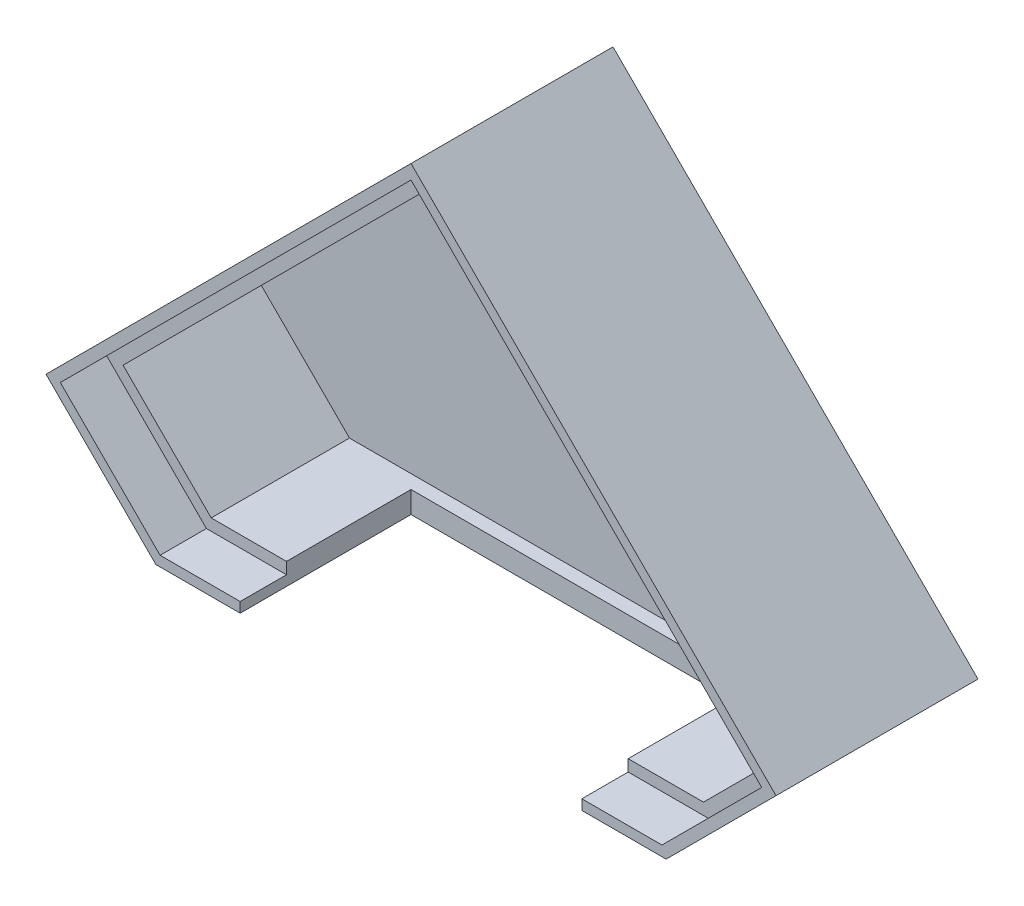
SolidWorks part; units mm, degrees
ref_plane "Спереди" through (0, 0, 0) normal (0, 0, 1) x (1, 0, 0)
ref_plane "Сверху" through (0, 0, 0) normal (0, 1, 0) x (1, 0, 0)
ref_plane "Справа" through (0, 0, 0) normal (1, 0, 0) x (0, 0, -1)
sketch "Эскиз1" plane through (0, 0, 0) normal (0, 0, 1) x (1, 0, 0)
  line L0 (-17, -12) -> (17, -12)
  line L1 (17, -12) -> (23.0901, -5.9099)
  line L2 (23.0901, -5.9099) -> (0, 17.1802)
  line L3 (0, 17.1802) -> (-23.0901, -5.9099)
  line L4 (-23.0901, -5.9099) -> (-17, -12)
  line L5 (16.5, -10.5) -> (-16.5, -10.5) construction
  dimension "D1" = 90
  dimension "D2" = 90
  dimension "D3" = 90
  dimension "D4" = 1.5
  dimension "D5" = 0.5
  dimension "D6" = 0.5
extrude "Вытянуть-Тонкостенный1" add sketch "Эскиз1" along normal blind 12.75 and the other way blind 12.75 thin
sketch "Эскиз2" plane through (0, 0, 12.75) normal (0, 0, 1) x (1, 0, 0)
  line L0 (25.2114, -5.9099) -> (0, 19.3015) construction
  line L1 (17.6213, -13.5) -> (25.2114, -5.9099) construction
  line L2 (-17.6213, -13.5) -> (17.6213, -13.5) construction
  line L3 (-25.2114, -5.9099) -> (-17.6213, -13.5) construction
  line L4 (0, 19.3015) -> (-25.2114, -5.9099) construction
  line L5 (25.2114, -5.9099) -> (0, 19.3015)
  line L6 (17.6213, -13.5) -> (25.2114, -5.9099)
  line L7 (-17.6213, -13.5) -> (17.6213, -13.5)
  line L8 (-25.2114, -5.9099) -> (-17.6213, -13.5)
  line L9 (0, 19.3015) -> (-25.2114, -5.9099)
extrude "Бобышка-Вытянуть1" add sketch "Эскиз2" along normal blind 1.2
sketch "Эскиз3" plane through (0, 0, -12.75) normal (0, 0, -1) x (-1, 0, 0)
  line L0 (0, 19.3015) -> (25.2114, -5.9099) construction
  line L1 (25.2114, -5.9099) -> (17.6213, -13.5) construction
  line L2 (17.6213, -13.5) -> (-17.6213, -13.5) construction
  line L3 (-17.6213, -13.5) -> (-25.2114, -5.9099) construction
  line L4 (-25.2114, -5.9099) -> (0, 19.3015) construction
  line L5 (0, 19.3015) -> (25.2114, -5.9099)
  line L6 (25.2114, -5.9099) -> (17.6213, -13.5)
  line L7 (17.6213, -13.5) -> (-17.6213, -13.5)
  line L8 (-17.6213, -13.5) -> (-25.2114, -5.9099)
  line L9 (-25.2114, -5.9099) -> (0, 19.3015)
extrude "Бобышка-Вытянуть2" add sketch "Эскиз3" along normal blind 1.2
sketch "Эскиз4" plane through (0, -13.5, 0) normal (0, -1, 0) x (1, 0, 0)
  line L0 (11.5, 11.5) -> (-11.5, 11.5) construction
  line L1 (-11.8, 11.8) -> (11.8, 11.8)
  line L2 (-11.8, 11.8) -> (-11.8, -11.8)
  line L3 (-11.8, -11.8) -> (11.8, -11.8)
  line L4 (11.8, 11.8) -> (11.8, -11.8)
  line L5 (-11.8, 11.8) -> (11.8, -11.8) construction
  line L6 (-11.8, -11.8) -> (11.8, 11.8) construction
  line L7 (11.5, -11.5) -> (11.5, 11.5) construction
  point P0 (0, 0)
  dimension "D1" = 0.3
  dimension "D2" = 0.3
extrude "Вырез-Вытянуть1" cut sketch "Эскиз4" against normal up to surface (1.5 mm away) up to face at (0, -12, 0)
sketch "Эскиз5" plane through (0, 0, 0) normal (1, 0, 0) x (0, 0, -1)
  line L0 (13.95, 19.3015) -> (-13.95, 19.3015) construction
  line L1 (0, 19.3015) -> (-13.95, 19.3015)
  line L2 (0, 19.3015) -> (0, -13.5)
  line L3 (0, -13.5) -> (-13.95, -13.5)
  line L4 (-13.95, 19.3015) -> (-13.95, -13.5)
extrude "Вырез-Вытянуть2" cut sketch "Эскиз5" against normal through all and the other way through all
sketch "Эскиз6" plane through (0, 0, 0) normal (0, 0, 1) x (1, 0, 0)
  line L0 (-11.8, -13.5) -> (11.8, -13.5) construction
  line L1 (0, 19.3015) -> (-25.2114, -5.9099) construction
  line L27 (-17.3314, -12.8) -> (17.3314, -12.8)
  line L28 (-24.2215, -5.9099) -> (-17.3314, -12.8)
  line L29 (0, 18.3115) -> (-24.2215, -5.9099)
  line L34 (17.3314, -12.8) -> (24.2215, -5.9099)
  line L35 (24.2215, -5.9099) -> (0, 18.3115)
  dimension "D1" = 0.7
  dimension "D2" = 0.7
extrude "Вырез-Вытянуть3" cut sketch "Эскиз6" against normal blind 3.2
